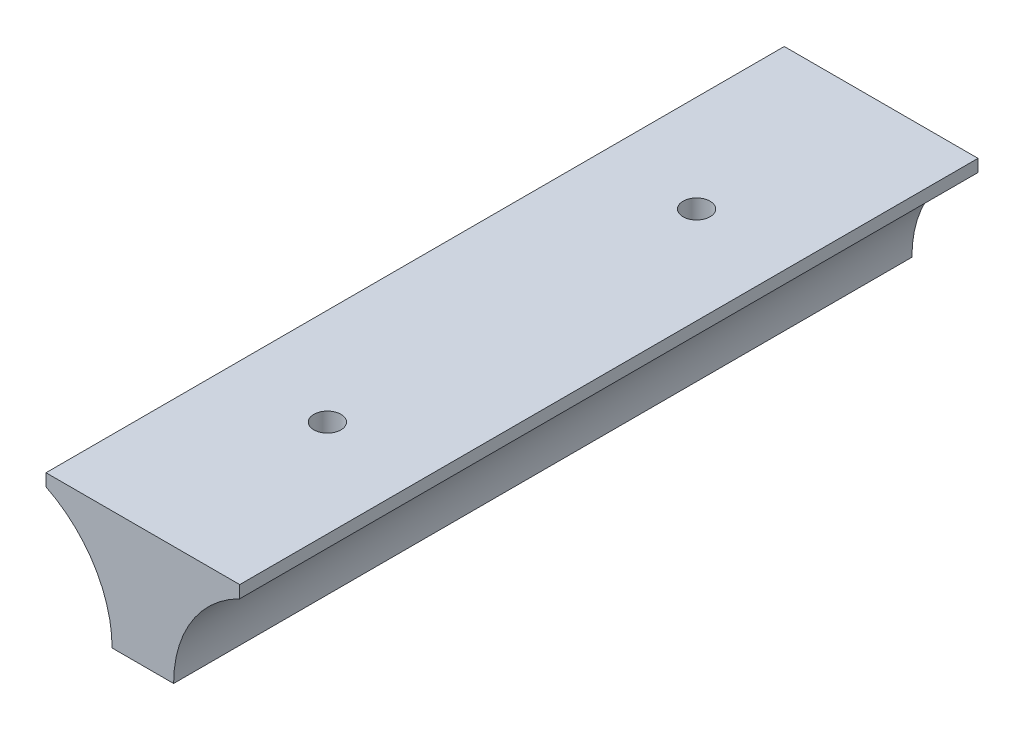
SolidWorks part; units mm, degrees
ref_plane "Front" through (0, 0, 0) normal (0, 0, 1) x (1, 0, 0)
ref_plane "Top" through (0, 0, 0) normal (0, 1, 0) x (1, 0, 0)
ref_plane "Right" through (0, 0, 0) normal (1, 0, 0) x (0, 0, -1)
sketch "Sketch1" plane through (0, 0, 0) normal (0, 0, 1) x (1, 0, 0)
  line L0 (-2.5, 0) -> (2.5, 0)
  line L1 (7.8722, 8.65) -> (7.8722, 9.65)
  line L2 (7.8722, 9.65) -> (-7.8722, 9.65)
  line L3 (-7.8722, 9.65) -> (-7.8722, 8.65)
  arc A0 (2.5, 0) -> (7.8722, 8.65) centre (12.15, 0) cw
  arc A1 (-2.5, 0) -> (-7.8722, 8.65) centre (-12.15, 0) ccw
  point P9 (0, 0)
  point P10 (0, 9.65)
  dimension "D1" = 9.65
  dimension "D2" = 9.65
  dimension "D3" = 5
  dimension "D4" = 1
extrude "Boss-Extrude1" add sketch "Sketch1" along normal blind 60
sketch "Sketch2" plane through (0, 9.65, 0) normal (0, 1, 0) x (1, 0, 0)
  line L0 (0, -60) -> (0, 0) construction
  line L1 (7.8722, -60) -> (-7.8722, -60) construction
  line L2 (7.8722, 0) -> (-7.8722, 0) construction
  point P6 (0, -45)
  point P7 (0, -15)
  dimension "D1" = 15
  dimension "D2" = 15
hole_wizard "Ø2.2 (2.2) Diameter Hole1" positions "3DSketch1" profile "Sketch3" hole size "Ø2.2" standard "ANSI Metric" end condition up to next
sketch3d "3DSketch1"
  point P0 (0, 9.65, 45)
  point P3 (0, 9.65, 15)
sketch "Sketch3" plane through (0, 9.65, 45) normal (1, 0, 0) x (0, 0, 1)
  line L0 (0, 0) -> (0, 9.65)
  line L1 (0, 9.65) -> (1.1, 9.65)
  line L2 (1.1, 9.65) -> (1.1, 0)
  line L5 (1.1, 0) -> (0, 0)
  line L11 (0, -6.35) -> (0, 107.95) construction
  dimension "Thru Hole Dia." = 2.2
  dimension "Thru Hole Depth" = 9.65
